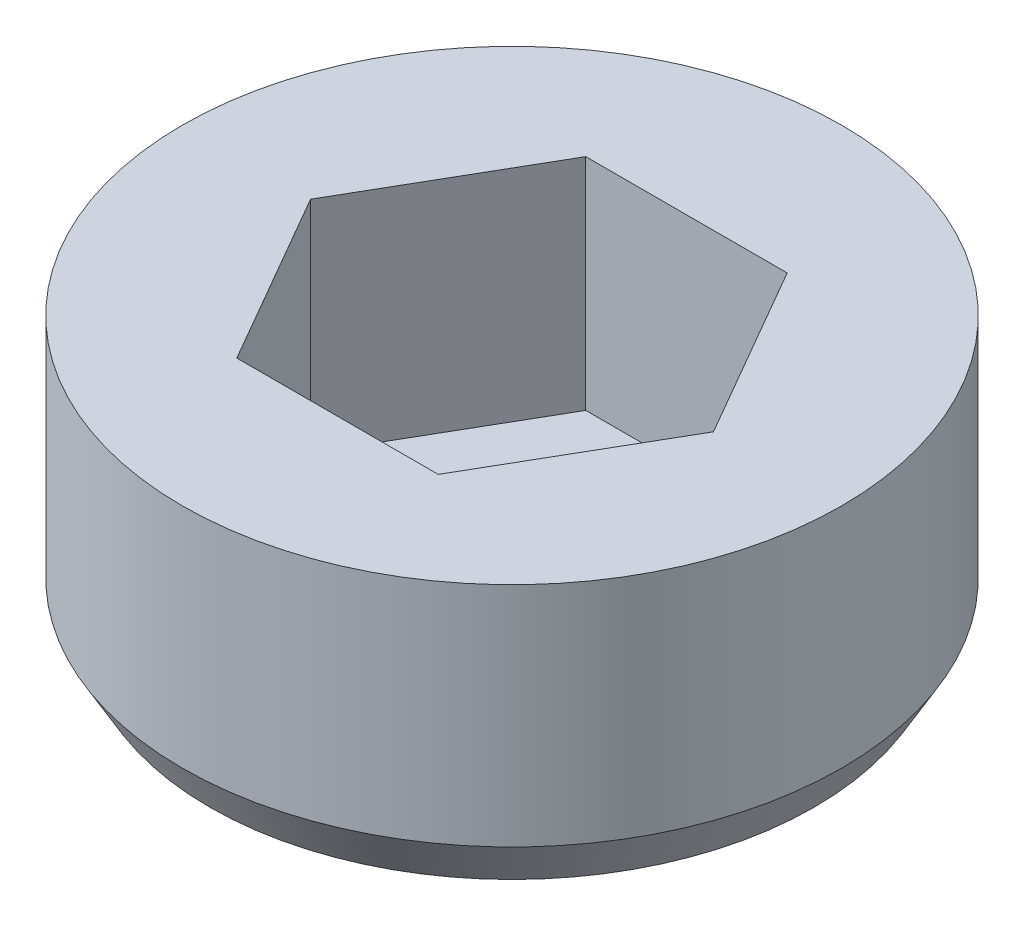
SolidWorks part; units mm, degrees
ref_plane "Front Plane" through (0, 0, 0) normal (0, 0, 1) x (1, 0, 0)
ref_plane "Top Plane" through (0, 0, 0) normal (0, 1, 0) x (1, 0, 0)
ref_plane "Right Plane" through (0, 0, 0) normal (1, 0, 0) x (0, 0, -1)
sketch "Sketch1" plane through (0, 0, 0) normal (0, 1, 0) x (1, 0, 0)
  circle A0 centre (0, 0) radius 3.1
  circle A1 centre (0, 0) radius 12
  dimension "D1" = 6.2
  dimension "D2" = 24
extrude "Boss-Extrude1" add sketch "Sketch1" along normal blind 10
sketch "Sketch2" plane through (0, 10, 0) normal (0, 1, 0) x (1, 0, 0)
  line L1 (7.3323, 0) -> (3.6662, 6.35)
  line L2 (3.6662, 6.35) -> (-3.6662, 6.35)
  line L3 (-3.6662, 6.35) -> (-7.3323, 0)
  line L4 (-7.3323, 0) -> (-3.6662, -6.35)
  line L5 (-3.6662, -6.35) -> (3.6662, -6.35)
  line L6 (3.6662, -6.35) -> (7.3323, 0)
  circle A0 centre (0, 0) radius 6.35 construction
  dimension "D1" = 12.7
extrude "Cut-Extrude1" cut sketch "Sketch2" against normal blind 8
chamfer "Chamfer1" distance 1 angle 60 1 edges at (0, 0, 12)
